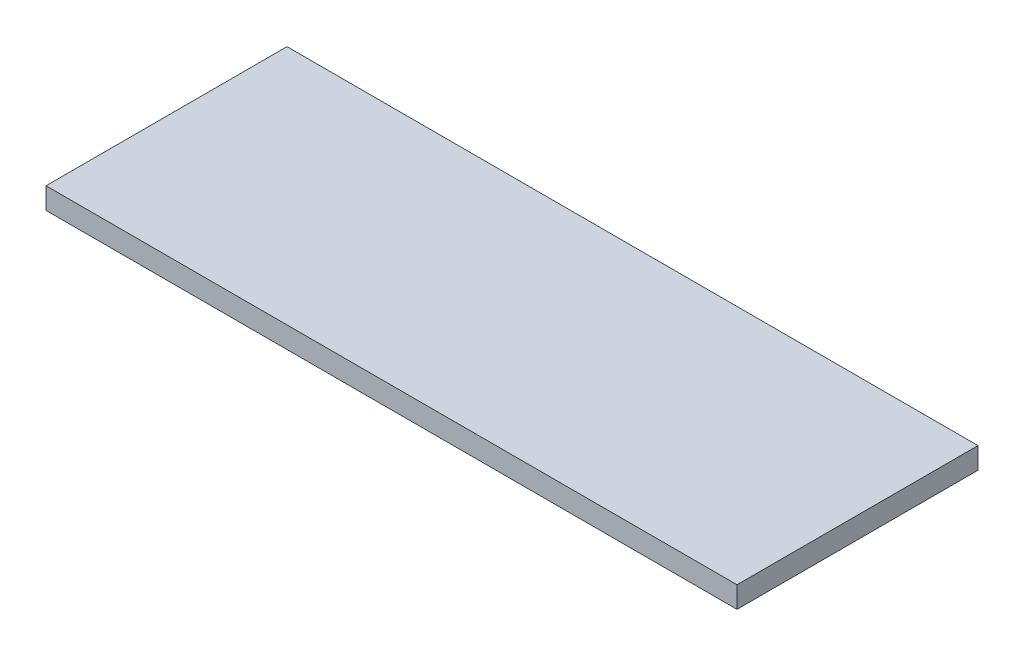
SolidWorks part; units mm, degrees
ref_plane "Front Plane" through (0, 0, 0) normal (0, 0, 1) x (1, 0, 0)
ref_plane "Top Plane" through (0, 0, 0) normal (0, 1, 0) x (1, 0, 0)
ref_plane "Right Plane" through (0, 0, 0) normal (1, 0, 0) x (0, 0, -1)
sketch "Sketch1" plane through (0, 0, 0) normal (0, 1, 0) x (1, 0, 0)
  line L1 (-15.7889, 4.8153) -> (15.7811, 4.8153)
  line L2 (-15.7889, 4.8153) -> (-15.7889, -6.1947)
  line L3 (-15.7889, -6.1947) -> (15.7811, -6.1947)
  line L4 (15.7811, 4.8153) -> (15.7811, -6.1947)
  dimension "D1" = 31.57
  dimension "D2" = 11.01
extrude "Boss-Extrude1" add sketch "Sketch1" along normal blind 0.9745
